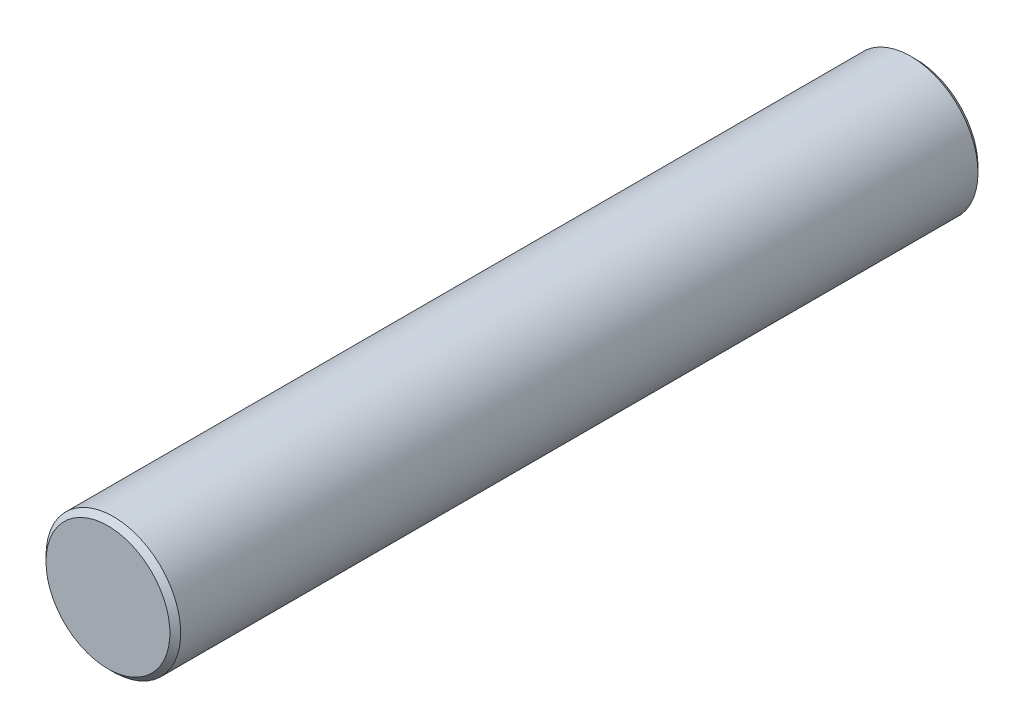
SolidWorks part; units mm, degrees
ref_plane "Front Plane" through (0, 0, 0) normal (0, 0, 1) x (1, 0, 0)
ref_plane "Top Plane" through (0, 0, 0) normal (0, 1, 0) x (1, 0, 0)
ref_plane "Right Plane" through (0, 0, 0) normal (1, 0, 0) x (0, 0, -1)
sketch "Sketch1" plane through (0, 0, 0) normal (0, 0, 1) x (1, 0, 0)
  circle A0 centre (0, 0) radius 7.9375
  dimension "D1" = 15.875
extrude "Boss-Extrude1" add sketch "Sketch1" along normal blind 95.25
chamfer "Chamfer1" distance 0.635 angle 45 2 edges at (7.9375, 0, 0) (7.9375, 0, 95.25)
